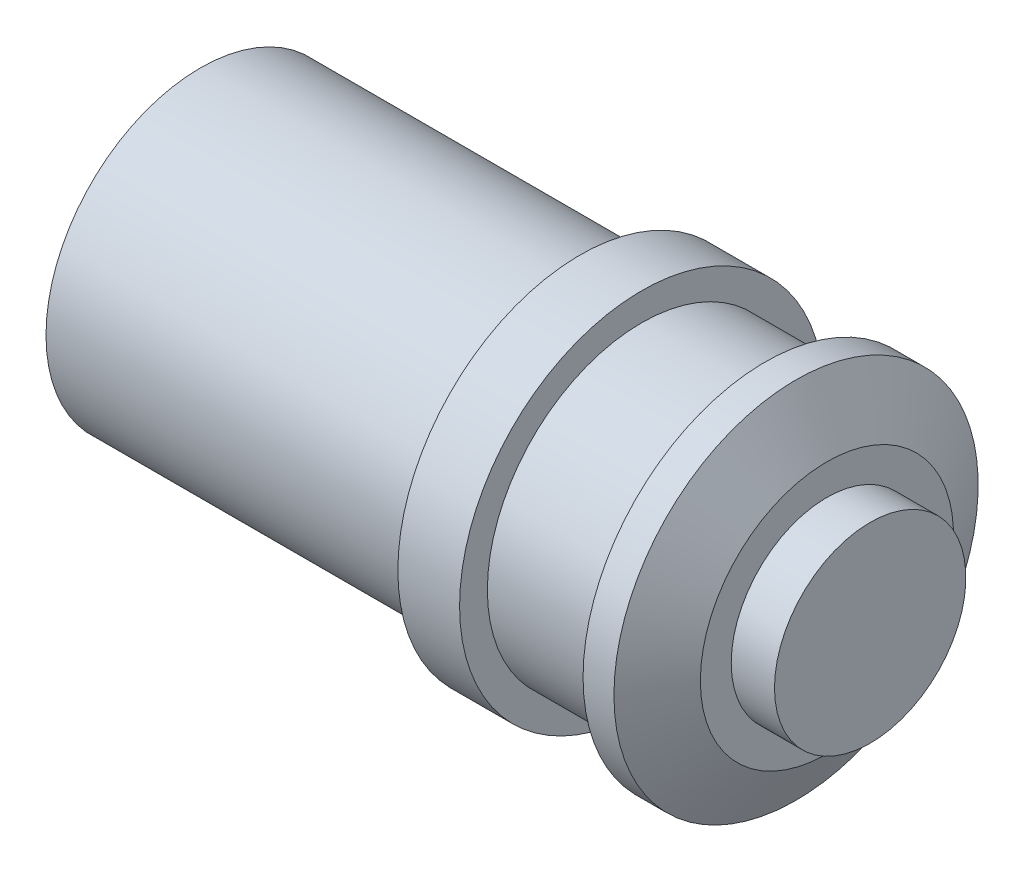
SolidWorks part; units mm, degrees
ref_plane "Front Plane" through (0, 0, 0) normal (0, 0, 1) x (1, 0, 0)
ref_plane "Top Plane" through (0, 0, 0) normal (0, 1, 0) x (1, 0, 0)
ref_plane "Right Plane" through (0, 0, 0) normal (1, 0, 0) x (0, 0, -1)
sketch "Sketch1" plane through (0, 0, 0) normal (0, 1, 0) x (1, 0, 0)
  line L0 (0, 0) -> (21.7, 0) construction
  line L1 (21.7, 0) -> (21.7, 3.1)
  line L2 (21.7, 3.1) -> (20.2986, 3.1)
  line L3 (20.2986, 3.1) -> (20.2986, 4.1)
  line L4 (20.2986, 4.1) -> (19.2986, 5.9)
  line L5 (19.2986, 5.9) -> (18.2986, 5.9)
  line L6 (18.2986, 5.9) -> (18.2986, 5)
  line L7 (18.2986, 5) -> (14.2986, 5)
  line L8 (14.2986, 5) -> (14.2986, 5.9)
  line L9 (14.2986, 5.9) -> (12.2986, 5.9)
  line L10 (12.2986, 5.9) -> (12.2986, 5)
  line L11 (12.2986, 5) -> (0, 5)
  line L12 (0, 5) -> (0, 0)
  line L13 (0, 0) -> (21.7, 0)
  dimension "D1" = 21.7
  dimension "D2" = 3.4014
  dimension "D3" = 5.9
  dimension "D4" = 5
  dimension "6.2/2" = 3.1
  dimension "D5" = 2
  dimension "4" = 4
  dimension "D6" = 1
  dimension "D7" = 2
  dimension "D8" = 1
revolve "Revolve1" add sketch "Sketch1" angle 360 about L0
